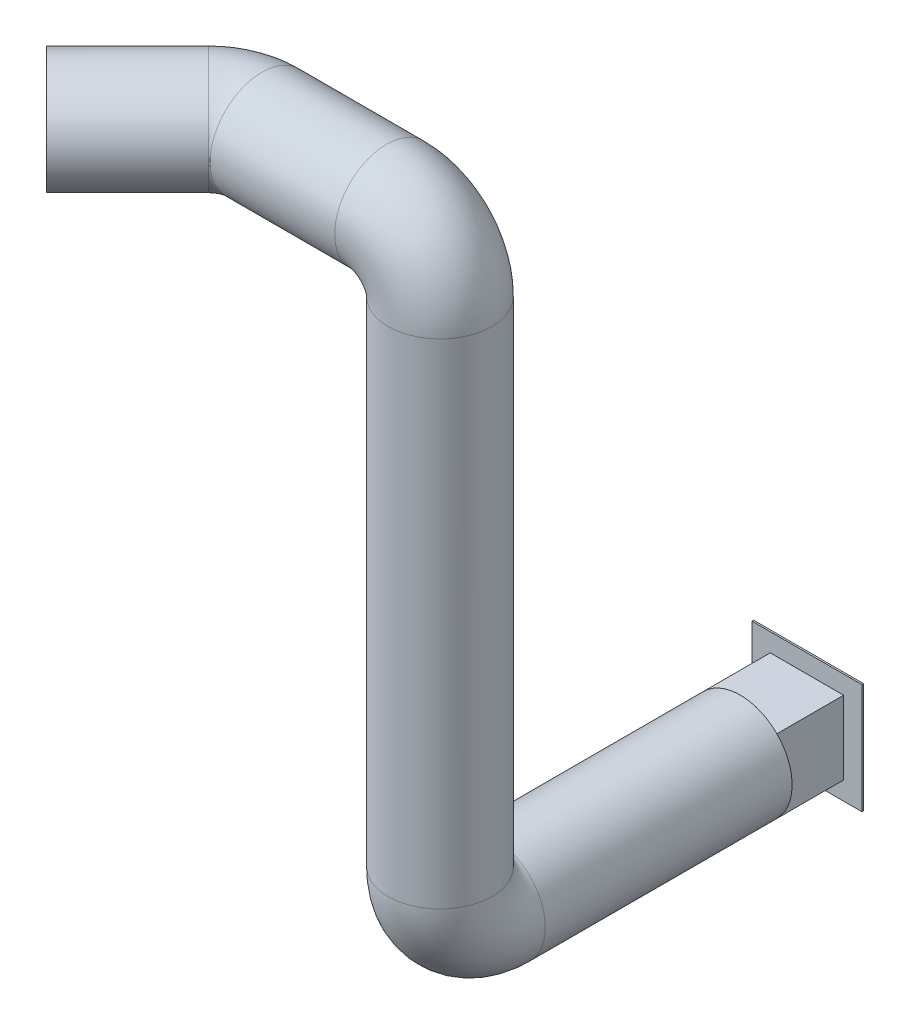
SolidWorks part; units mm, degrees
ref_plane "Alzado" through (0, 0, 0) normal (0, 0, 1) x (1, 0, 0)
ref_plane "Planta" through (0, 0, 0) normal (0, 1, 0) x (1, 0, 0)
ref_plane "Vista lateral" through (0, 0, 0) normal (1, 0, 0) x (0, 0, -1)
sketch "Croquis1" plane through (0, 0, 0) normal (0, 0, 1) x (1, 0, 0)
  line L0 (82.5, 0) -> (82.5, -165) construction
  line L1 (0, 0) -> (165, 0)
  line L2 (0, 0) -> (0, -165)
  line L3 (0, -165) -> (165, -165)
  line L4 (165, 0) -> (165, -165)
  line L6 (30, -135) -> (135, -135)
  line L7 (30, -135) -> (30, -30)
  line L8 (30, -30) -> (135, -30)
  line L9 (135, -135) -> (135, -30)
  line L10 (30, -135) -> (135, -30) construction
  line L11 (30, -30) -> (135, -135) construction
  point P8 (82.5, -82.5)
  dimension "D1" = 165
  dimension "D2" = 165
  dimension "D3" = 30
  dimension "D4" = 30
extrude "Saliente-Extruir1" add sketch "Croquis1" along normal blind 2.5
sketch "Croquis2" plane through (0, 0, 2.5) normal (0, 0, 1) x (1, 0, 0)
  line L0 (27.5, -27.5) -> (27.5, -137.5)
  line L1 (30, -30) -> (135, -30)
  line L2 (30, -30) -> (30, -135)
  line L3 (30, -135) -> (135, -135)
  line L4 (135, -30) -> (135, -135)
  line L5 (27.5, -137.5) -> (137.5, -137.5)
  line L6 (137.5, -27.5) -> (137.5, -137.5)
  line L7 (27.5, -27.5) -> (137.5, -27.5)
  dimension "D1" = 2.5
extrude "Saliente-Extruir2" add sketch "Croquis2" along normal blind 100
sketch "Croquis3" plane through (0, 0, 102.5) normal (0, 0, 1) x (1, 0, 0)
  line L0 (82.5, -30) -> (82.5, -135) construction
  line L1 (135, -30) -> (30, -30) construction
  line L2 (30, -135) -> (135, -135) construction
  circle A0 centre (82.5, -82.5) radius 77.7817
extrude "Saliente-Extruir3" add sketch "Croquis3" along normal blind 100
sketch3d "Croquis3D1"
  line L0 (82.5, -82.5, 202.5) -> (82.5, -82.5, 472.5)
  line L1 (82.5, -82.5, 202.5) -> (82.5, -82.5, 102.5) construction
  line L3 (82.5, -2.5, 552.5) -> (82.5, 737.5, 552.5)
  line L4 (2.5, 817.5, 552.5) -> (-184.3629, 817.5, 552.5)
  line L5 (-217.5, 817.5, 552.5) -> (-217.5, 817.5, 697.5) construction
  line L6 (-217.5, 817.5, 697.5) -> (-362.5, 817.5, 697.5) construction
  line L7 (-362.5, 817.5, 697.5) -> (-240.9315, 817.5, 575.9315)
  arc A0 (-184.3629, 817.5, 552.5) -> (-240.9315, 817.5, 575.9315) centre (-184.3629, 817.5, 632.5) ccw
  arc A1 (82.5, 737.5, 552.5) -> (2.5, 817.5, 552.5) centre (2.5, 737.5, 552.5) ccw
  arc A2 (82.5, -82.5, 472.5) -> (82.5, -2.5, 552.5) centre (82.5, -2.5, 472.5) ccw
  point P10 (-217.5, 717.5, 552.5)
  point P11 (-217.5, 817.5, 552.5)
  point P13 (-184.3629, 897.5, 632.5)
  point P15 (82.5, 717.5, 552.5)
  point P17 (82.5, 817.5, 552.5)
  point P18 (2.5, 737.5, 632.5)
  point P19 (82.5, 617.5, 552.5)
  point P22 (82.5, -82.5, 552.5)
  point P23 (2.5, -2.5, 472.5)
  dimension "D6" = 145
  dimension "D8" = 80
  dimension "D1" = 350
  dimension "D4" = 900
  dimension "D2" = 100
  dimension "D3" = 300
  dimension "D5" = 300
  dimension "D7" = 145
sketch "Croquis5" plane through (0, 0, 202.5) normal (0, 0, 1) x (1, 0, 0)
  circle A0 centre (82.5, -82.5) radius 77.7817
sweep "Barrer1" add profiles "Croquis5" path "Croquis3D1"
